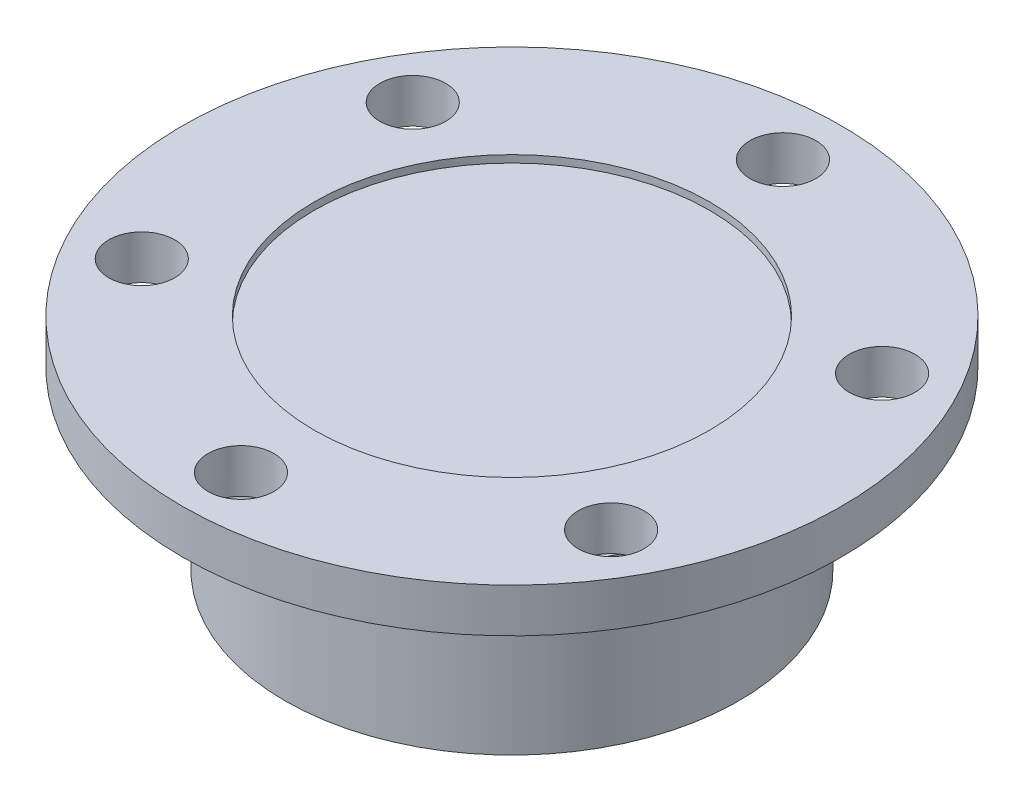
SolidWorks part; units mm, degrees
ref_plane "Front Plane" through (0, 0, 0) normal (0, 0, 1) x (1, 0, 0)
ref_plane "Top Plane" through (0, 0, 0) normal (0, 1, 0) x (1, 0, 0)
ref_plane "Right Plane" through (0, 0, 0) normal (1, 0, 0) x (0, 0, -1)
sketch "Sketch1" plane through (0, 0, 0) normal (0, 0, 1) x (1, 0, 0)
  line L0 (0, 30.6188) -> (0, -35.2308) construction
  line L2 (-45, 30) -> (-45, 24)
  line L3 (-45, 24) -> (-29.5, 24)
  line L4 (-29.5, 24) -> (-29.5, 22.5)
  line L5 (-29.5, 22.5) -> (-31, 22.5)
  line L6 (-31, 22.5) -> (-31, 0)
  line L7 (-31, 0) -> (-26.6727, 0)
  line L8 (-26.6727, 0) -> (-22, 26.5)
  line L9 (-22, 26.5) -> (0, 26.5)
  line L11 (-45, 30) -> (-27, 30)
  line L12 (-27, 30) -> (-27, 29)
  line L13 (-27, 29) -> (0, 29)
  line L14 (0, 29) -> (0, 26.5)
  dimension "D1" = 31
  dimension "D2" = 45
  dimension "D3" = 18
  dimension "D4" = 100
  dimension "D5" = 1.5
  dimension "D6" = 15.5
  dimension "D7" = 1.5
  dimension "D8" = 24
  dimension "D9" = 22
  dimension "D10" = 1
  dimension "D11" = 2.5
  dimension "D12" = 6
revolve "Revolve1" add sketch "Sketch1" angle 360 about L0
sketch "Sketch2" plane through (0, 30, 0) normal (0, 1, 0) x (1, 0, 0)
  line L0 (-53.4517, 0) -> (69.7526, 0) construction
  line L1 (0, 51.0634) -> (0, -55.84) construction
  circle A0 centre (0, 37) radius 4.5
  circle A1 centre (32.0429, 18.5) radius 4.5
  circle A2 centre (32.0429, -18.5) radius 4.5
  circle A3 centre (0, -37) radius 4.5
  circle A4 centre (-32.0429, -18.5) radius 4.5
  circle A5 centre (-32.0429, 18.5) radius 4.5
  point P19 (0, 0)
  dimension "D1" = 9
  dimension "D2" = 37
  dimension "D3" = 6
extrude "Cut-Extrude1" cut sketch "Sketch2" against normal up to next
